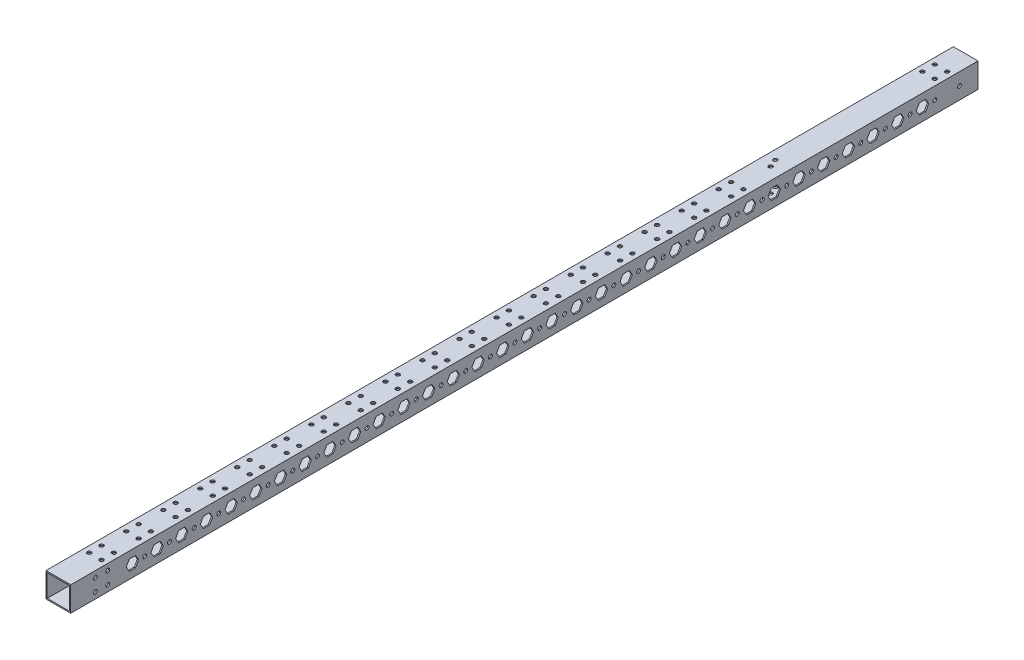
SolidWorks part; units mm, degrees
ref_plane "前视基准面" through (0, 0, 0) normal (0, 0, 1) x (1, 0, 0)
ref_plane "上视基准面" through (0, 0, 0) normal (0, 1, 0) x (1, 0, 0)
ref_plane "右视基准面" through (0, 0, 0) normal (1, 0, 0) x (0, 0, -1)
other "Configuration Table"
sketch "草图1" plane through (0, 0, 0) normal (0, 0, 1) x (1, 0, 0)
  line L1 (0, 0) -> (20, 0)
  line L2 (0, 0) -> (0, -20)
  line L3 (0, -20) -> (20, -20)
  line L4 (20, 0) -> (20, -20)
  dimension "D1" = 20
  dimension "D2" = 20
extrude "拉伸-薄壁1" add sketch "草图1" along normal blind 735 thin
sketch "草图2" plane through (20, 0, 0) normal (1, 0, 0) x (0, 0, -1)
  line L0 (-10, 0) -> (-10, -20) construction
  line L1 (0, -20) -> (0, 0) construction
  line L2 (-15, -10) -> (0, -10) construction
  line L3 (-710, 0) -> (-710, -20) construction
  line L4 (-735, 0) -> (0, 0) construction
  line L5 (-735, -20) -> (0, -20) construction
  line L6 (-735, -20) -> (-735, 0) construction
  line L7 (-710, -10) -> (-735, -10) construction
  line L8 (-20, 0) -> (-20, -20) construction
  line L9 (-35, -10) -> (-55, -10) construction
  line L10 (-47.5, -5.6699) -> (-50, -10)
  line L11 (-50, -10) -> (-47.5, -14.3301)
  line L12 (-47.5, -14.3301) -> (-42.5, -14.3301)
  line L13 (-42.5, -14.3301) -> (-40, -10)
  line L14 (-40, -10) -> (-42.5, -5.6699)
  line L15 (-42.5, -5.6699) -> (-47.5, -5.6699)
  line L16 (-62.5, -5.6699) -> (-67.5, -5.6699)
  line L17 (-60, -10) -> (-62.5, -5.6699)
  line L18 (-62.5, -14.3301) -> (-60, -10)
  line L19 (-67.5, -14.3301) -> (-62.5, -14.3301)
  line L20 (-67.5, -5.6699) -> (-70, -10)
  line L21 (-70, -10) -> (-67.5, -14.3301)
  line L22 (-82.5, -5.6699) -> (-87.5, -5.6699)
  line L23 (-80, -10) -> (-82.5, -5.6699)
  line L24 (-82.5, -14.3301) -> (-80, -10)
  line L25 (-87.5, -14.3301) -> (-82.5, -14.3301)
  line L26 (-87.5, -5.6699) -> (-90, -10)
  line L27 (-90, -10) -> (-87.5, -14.3301)
  line L28 (-102.5, -5.6699) -> (-107.5, -5.6699)
  line L29 (-100, -10) -> (-102.5, -5.6699)
  line L30 (-102.5, -14.3301) -> (-100, -10)
  line L31 (-107.5, -14.3301) -> (-102.5, -14.3301)
  line L32 (-107.5, -5.6699) -> (-110, -10)
  line L33 (-110, -10) -> (-107.5, -14.3301)
  line L34 (-122.5, -5.6699) -> (-127.5, -5.6699)
  line L35 (-120, -10) -> (-122.5, -5.6699)
  line L36 (-122.5, -14.3301) -> (-120, -10)
  line L37 (-127.5, -14.3301) -> (-122.5, -14.3301)
  line L38 (-127.5, -5.6699) -> (-130, -10)
  line L39 (-130, -10) -> (-127.5, -14.3301)
  line L40 (-142.5, -5.6699) -> (-147.5, -5.6699)
  line L41 (-140, -10) -> (-142.5, -5.6699)
  line L42 (-142.5, -14.3301) -> (-140, -10)
  line L43 (-147.5, -14.3301) -> (-142.5, -14.3301)
  line L44 (-147.5, -5.6699) -> (-150, -10)
  line L45 (-150, -10) -> (-147.5, -14.3301)
  line L46 (-162.5, -5.6699) -> (-167.5, -5.6699)
  line L47 (-160, -10) -> (-162.5, -5.6699)
  line L48 (-162.5, -14.3301) -> (-160, -10)
  line L49 (-167.5, -14.3301) -> (-162.5, -14.3301)
  line L50 (-167.5, -5.6699) -> (-170, -10)
  line L51 (-170, -10) -> (-167.5, -14.3301)
  line L52 (-182.5, -5.6699) -> (-187.5, -5.6699)
  line L53 (-180, -10) -> (-182.5, -5.6699)
  line L54 (-182.5, -14.3301) -> (-180, -10)
  line L55 (-187.5, -14.3301) -> (-182.5, -14.3301)
  line L56 (-187.5, -5.6699) -> (-190, -10)
  line L57 (-190, -10) -> (-187.5, -14.3301)
  line L58 (-202.5, -5.6699) -> (-207.5, -5.6699)
  line L59 (-200, -10) -> (-202.5, -5.6699)
  line L60 (-202.5, -14.3301) -> (-200, -10)
  line L61 (-207.5, -14.3301) -> (-202.5, -14.3301)
  line L62 (-207.5, -5.6699) -> (-210, -10)
  line L63 (-210, -10) -> (-207.5, -14.3301)
  line L64 (-222.5, -5.6699) -> (-227.5, -5.6699)
  line L65 (-220, -10) -> (-222.5, -5.6699)
  line L66 (-222.5, -14.3301) -> (-220, -10)
  line L67 (-227.5, -14.3301) -> (-222.5, -14.3301)
  line L68 (-227.5, -5.6699) -> (-230, -10)
  line L69 (-230, -10) -> (-227.5, -14.3301)
  line L70 (-242.5, -5.6699) -> (-247.5, -5.6699)
  line L71 (-240, -10) -> (-242.5, -5.6699)
  line L72 (-242.5, -14.3301) -> (-240, -10)
  line L73 (-247.5, -14.3301) -> (-242.5, -14.3301)
  line L74 (-247.5, -5.6699) -> (-250, -10)
  line L75 (-250, -10) -> (-247.5, -14.3301)
  line L76 (-262.5, -5.6699) -> (-267.5, -5.6699)
  line L77 (-260, -10) -> (-262.5, -5.6699)
  line L78 (-262.5, -14.3301) -> (-260, -10)
  line L79 (-267.5, -14.3301) -> (-262.5, -14.3301)
  line L80 (-267.5, -5.6699) -> (-270, -10)
  line L81 (-270, -10) -> (-267.5, -14.3301)
  line L82 (-282.5, -5.6699) -> (-287.5, -5.6699)
  line L83 (-280, -10) -> (-282.5, -5.6699)
  line L84 (-282.5, -14.3301) -> (-280, -10)
  line L85 (-287.5, -14.3301) -> (-282.5, -14.3301)
  line L86 (-287.5, -5.6699) -> (-290, -10)
  line L87 (-290, -10) -> (-287.5, -14.3301)
  line L88 (-302.5, -5.6699) -> (-307.5, -5.6699)
  line L89 (-300, -10) -> (-302.5, -5.6699)
  line L90 (-302.5, -14.3301) -> (-300, -10)
  line L91 (-307.5, -14.3301) -> (-302.5, -14.3301)
  line L92 (-307.5, -5.6699) -> (-310, -10)
  line L93 (-310, -10) -> (-307.5, -14.3301)
  line L94 (-322.5, -5.6699) -> (-327.5, -5.6699)
  line L95 (-320, -10) -> (-322.5, -5.6699)
  line L96 (-322.5, -14.3301) -> (-320, -10)
  line L97 (-327.5, -14.3301) -> (-322.5, -14.3301)
  line L98 (-327.5, -5.6699) -> (-330, -10)
  line L99 (-330, -10) -> (-327.5, -14.3301)
  line L100 (-342.5, -5.6699) -> (-347.5, -5.6699)
  line L101 (-340, -10) -> (-342.5, -5.6699)
  line L102 (-342.5, -14.3301) -> (-340, -10)
  line L103 (-347.5, -14.3301) -> (-342.5, -14.3301)
  line L104 (-347.5, -5.6699) -> (-350, -10)
  line L105 (-350, -10) -> (-347.5, -14.3301)
  line L106 (-362.5, -5.6699) -> (-367.5, -5.6699)
  line L107 (-360, -10) -> (-362.5, -5.6699)
  line L108 (-362.5, -14.3301) -> (-360, -10)
  line L109 (-367.5, -14.3301) -> (-362.5, -14.3301)
  line L110 (-367.5, -5.6699) -> (-370, -10)
  line L111 (-370, -10) -> (-367.5, -14.3301)
  line L112 (-382.5, -5.6699) -> (-387.5, -5.6699)
  line L113 (-380, -10) -> (-382.5, -5.6699)
  line L114 (-382.5, -14.3301) -> (-380, -10)
  line L115 (-387.5, -14.3301) -> (-382.5, -14.3301)
  line L116 (-387.5, -5.6699) -> (-390, -10)
  line L117 (-390, -10) -> (-387.5, -14.3301)
  line L118 (-402.5, -5.6699) -> (-407.5, -5.6699)
  line L119 (-400, -10) -> (-402.5, -5.6699)
  line L120 (-402.5, -14.3301) -> (-400, -10)
  line L121 (-407.5, -14.3301) -> (-402.5, -14.3301)
  line L122 (-407.5, -5.6699) -> (-410, -10)
  line L123 (-410, -10) -> (-407.5, -14.3301)
  line L124 (-422.5, -5.6699) -> (-427.5, -5.6699)
  line L125 (-420, -10) -> (-422.5, -5.6699)
  line L126 (-422.5, -14.3301) -> (-420, -10)
  line L127 (-427.5, -14.3301) -> (-422.5, -14.3301)
  line L128 (-427.5, -5.6699) -> (-430, -10)
  line L129 (-430, -10) -> (-427.5, -14.3301)
  line L130 (-442.5, -5.6699) -> (-447.5, -5.6699)
  line L131 (-440, -10) -> (-442.5, -5.6699)
  line L132 (-442.5, -14.3301) -> (-440, -10)
  line L133 (-447.5, -14.3301) -> (-442.5, -14.3301)
  line L134 (-447.5, -5.6699) -> (-450, -10)
  line L135 (-450, -10) -> (-447.5, -14.3301)
  line L136 (-462.5, -5.6699) -> (-467.5, -5.6699)
  line L137 (-460, -10) -> (-462.5, -5.6699)
  line L138 (-462.5, -14.3301) -> (-460, -10)
  line L139 (-467.5, -14.3301) -> (-462.5, -14.3301)
  line L140 (-467.5, -5.6699) -> (-470, -10)
  line L141 (-470, -10) -> (-467.5, -14.3301)
  line L142 (-482.5, -5.6699) -> (-487.5, -5.6699)
  line L143 (-480, -10) -> (-482.5, -5.6699)
  line L144 (-482.5, -14.3301) -> (-480, -10)
  line L145 (-487.5, -14.3301) -> (-482.5, -14.3301)
  line L146 (-487.5, -5.6699) -> (-490, -10)
  line L147 (-490, -10) -> (-487.5, -14.3301)
  line L148 (-502.5, -5.6699) -> (-507.5, -5.6699)
  line L149 (-500, -10) -> (-502.5, -5.6699)
  line L150 (-502.5, -14.3301) -> (-500, -10)
  line L151 (-507.5, -14.3301) -> (-502.5, -14.3301)
  line L152 (-507.5, -5.6699) -> (-510, -10)
  line L153 (-510, -10) -> (-507.5, -14.3301)
  line L154 (-522.5, -5.6699) -> (-527.5, -5.6699)
  line L155 (-520, -10) -> (-522.5, -5.6699)
  line L156 (-522.5, -14.3301) -> (-520, -10)
  line L157 (-527.5, -14.3301) -> (-522.5, -14.3301)
  line L158 (-527.5, -5.6699) -> (-530, -10)
  line L159 (-530, -10) -> (-527.5, -14.3301)
  line L160 (-542.5, -5.6699) -> (-547.5, -5.6699)
  line L161 (-540, -10) -> (-542.5, -5.6699)
  line L162 (-542.5, -14.3301) -> (-540, -10)
  line L163 (-547.5, -14.3301) -> (-542.5, -14.3301)
  line L164 (-547.5, -5.6699) -> (-550, -10)
  line L165 (-550, -10) -> (-547.5, -14.3301)
  line L166 (-562.5, -5.6699) -> (-567.5, -5.6699)
  line L167 (-560, -10) -> (-562.5, -5.6699)
  line L168 (-562.5, -14.3301) -> (-560, -10)
  line L169 (-567.5, -14.3301) -> (-562.5, -14.3301)
  line L170 (-567.5, -5.6699) -> (-570, -10)
  line L171 (-570, -10) -> (-567.5, -14.3301)
  line L172 (-582.5, -5.6699) -> (-587.5, -5.6699)
  line L173 (-580, -10) -> (-582.5, -5.6699)
  line L174 (-582.5, -14.3301) -> (-580, -10)
  line L175 (-587.5, -14.3301) -> (-582.5, -14.3301)
  line L176 (-587.5, -5.6699) -> (-590, -10)
  line L177 (-590, -10) -> (-587.5, -14.3301)
  line L178 (-602.5, -5.6699) -> (-607.5, -5.6699)
  line L179 (-600, -10) -> (-602.5, -5.6699)
  line L180 (-602.5, -14.3301) -> (-600, -10)
  line L181 (-607.5, -14.3301) -> (-602.5, -14.3301)
  line L182 (-607.5, -5.6699) -> (-610, -10)
  line L183 (-610, -10) -> (-607.5, -14.3301)
  line L184 (-622.5, -5.6699) -> (-627.5, -5.6699)
  line L185 (-620, -10) -> (-622.5, -5.6699)
  line L186 (-622.5, -14.3301) -> (-620, -10)
  line L187 (-627.5, -14.3301) -> (-622.5, -14.3301)
  line L188 (-627.5, -5.6699) -> (-630, -10)
  line L189 (-630, -10) -> (-627.5, -14.3301)
  line L190 (-642.5, -5.6699) -> (-647.5, -5.6699)
  line L191 (-640, -10) -> (-642.5, -5.6699)
  line L192 (-642.5, -14.3301) -> (-640, -10)
  line L193 (-647.5, -14.3301) -> (-642.5, -14.3301)
  line L194 (-647.5, -5.6699) -> (-650, -10)
  line L195 (-650, -10) -> (-647.5, -14.3301)
  line L196 (-662.5, -5.6699) -> (-667.5, -5.6699)
  line L197 (-660, -10) -> (-662.5, -5.6699)
  line L198 (-662.5, -14.3301) -> (-660, -10)
  line L199 (-667.5, -14.3301) -> (-662.5, -14.3301)
  line L200 (-667.5, -5.6699) -> (-670, -10)
  line L201 (-670, -10) -> (-667.5, -14.3301)
  line L202 (-682.5, -5.6699) -> (-687.5, -5.6699)
  line L203 (-680, -10) -> (-682.5, -5.6699)
  line L204 (-682.5, -14.3301) -> (-680, -10)
  line L205 (-687.5, -14.3301) -> (-682.5, -14.3301)
  line L206 (-687.5, -5.6699) -> (-690, -10)
  line L207 (-690, -10) -> (-687.5, -14.3301)
  circle A34 centre (-715, -5) radius 1.575
  circle A35 centre (-705, -5) radius 1.575
  circle A36 centre (-705, -15) radius 1.575
  circle A37 centre (-715, -15) radius 1.575
  circle A42 centre (-55, -10) radius 1.575
  circle A43 centre (-75, -10) radius 1.575
  circle A44 centre (-95, -10) radius 1.575
  circle A45 centre (-115, -10) radius 1.575
  circle A46 centre (-135, -10) radius 1.575
  circle A47 centre (-155, -10) radius 1.575
  circle A48 centre (-175, -10) radius 1.575
  circle A49 centre (-195, -10) radius 1.575
  circle A50 centre (-215, -10) radius 1.575
  circle A51 centre (-235, -10) radius 1.575
  circle A52 centre (-255, -10) radius 1.575
  circle A53 centre (-275, -10) radius 1.575
  circle A54 centre (-295, -10) radius 1.575
  circle A55 centre (-315, -10) radius 1.575
  circle A56 centre (-335, -10) radius 1.575
  circle A57 centre (-355, -10) radius 1.575
  circle A58 centre (-375, -10) radius 1.575
  circle A59 centre (-395, -10) radius 1.575
  circle A60 centre (-415, -10) radius 1.575
  circle A61 centre (-435, -10) radius 1.575
  circle A62 centre (-455, -10) radius 1.575
  circle A63 centre (-475, -10) radius 1.575
  circle A64 centre (-495, -10) radius 1.575
  circle A65 centre (-515, -10) radius 1.575
  circle A67 centre (-35, -10) radius 1.575
  circle A100 centre (-535, -10) radius 1.575
  circle A101 centre (-555, -10) radius 1.575
  circle A102 centre (-575, -10) radius 1.575
  circle A103 centre (-595, -10) radius 1.575
  circle A104 centre (-615, -10) radius 1.575
  circle A105 centre (-635, -10) radius 1.575
  circle A106 centre (-655, -10) radius 1.575
  circle A107 centre (-675, -10) radius 1.575
  circle A108 centre (-15, -10) radius 1.575
  circle A113 centre (-45, -10) radius 4.3301 construction
  circle A114 centre (-65, -10) radius 4.3301 construction
  circle A115 centre (-85, -10) radius 4.3301 construction
  circle A116 centre (-105, -10) radius 4.3301 construction
  circle A117 centre (-125, -10) radius 4.3301 construction
  circle A118 centre (-145, -10) radius 4.3301 construction
  circle A119 centre (-165, -10) radius 4.3301 construction
  circle A120 centre (-185, -10) radius 4.3301 construction
  circle A121 centre (-205, -10) radius 4.3301 construction
  circle A122 centre (-225, -10) radius 4.3301 construction
  circle A123 centre (-245, -10) radius 4.3301 construction
  circle A124 centre (-265, -10) radius 4.3301 construction
  circle A125 centre (-285, -10) radius 4.3301 construction
  circle A126 centre (-305, -10) radius 4.3301 construction
  circle A127 centre (-325, -10) radius 4.3301 construction
  circle A128 centre (-345, -10) radius 4.3301 construction
  circle A129 centre (-365, -10) radius 4.3301 construction
  circle A130 centre (-385, -10) radius 4.3301 construction
  circle A131 centre (-405, -10) radius 4.3301 construction
  circle A132 centre (-425, -10) radius 4.3301 construction
  circle A133 centre (-445, -10) radius 4.3301 construction
  circle A134 centre (-465, -10) radius 4.3301 construction
  circle A135 centre (-485, -10) radius 4.3301 construction
  circle A136 centre (-505, -10) radius 4.3301 construction
  circle A137 centre (-525, -10) radius 4.3301 construction
  circle A138 centre (-545, -10) radius 4.3301 construction
  circle A139 centre (-565, -10) radius 4.3301 construction
  circle A140 centre (-585, -10) radius 4.3301 construction
  circle A141 centre (-605, -10) radius 4.3301 construction
  circle A142 centre (-625, -10) radius 4.3301 construction
  circle A143 centre (-645, -10) radius 4.3301 construction
  circle A144 centre (-665, -10) radius 4.3301 construction
  circle A145 centre (-685, -10) radius 4.3301 construction
  dimension "D2" = 3.15
  dimension "D5" = 3.15
  dimension "D8" = 10
  dimension "D12" = 3.15
  dimension "D4" = 25
  dimension "D3" = 35
  dimension "D6" = 5
  dimension "D7" = 5
  dimension "D9" = 10
  dimension "D10" = 5
  dimension "D11" = 20
  dimension "D13" = 33
  dimension "D14" = 20
  dimension "D15" = 15
  dimension "D16" = 20
extrude "切除-拉伸1" cut sketch "草图2" against normal through all
sketch "草图3" plane through (0, 0, 0) normal (0, 1, 0) x (1, 0, 0)
  line L0 (0, -400) -> (20, -400) construction
  line L1 (0, -735) -> (0, 0) construction
  line L2 (20, -735) -> (20, 0) construction
  line L3 (20, -735) -> (0, -735) construction
  line L4 (10, -400) -> (10, -735) construction
  line L5 (20, 0) -> (0, 0) construction
  line L6 (0, -25) -> (20, -25) construction
  line L7 (0, -158) -> (20, -158) construction
  line L8 (10, -158) -> (10, -146) construction
  line L9 (10, -146) -> (5, -146) construction
  line L10 (5, -146) -> (10, -158) construction
  circle A0 centre (5, -405) radius 1.6
  circle A1 centre (15, -405) radius 1.6
  circle A2 centre (15, -395) radius 1.6
  circle A3 centre (5, -395) radius 1.6
  circle A4 centre (5, -30) radius 1.6
  circle A5 centre (15, -30) radius 1.6
  circle A6 centre (15, -20) radius 1.6
  circle A7 centre (5, -20) radius 1.6
  circle A8 centre (10, -158) radius 1.6
  circle A9 centre (7.3077, -151.5385) radius 1.575
  circle A10 centre (5, -425) radius 1.6
  circle A11 centre (15, -425) radius 1.6
  circle A12 centre (15, -435) radius 1.6
  circle A13 centre (5, -435) radius 1.6
  circle A14 centre (5, -455) radius 1.6
  circle A15 centre (15, -455) radius 1.6
  circle A16 centre (15, -465) radius 1.6
  circle A17 centre (5, -465) radius 1.6
  circle A18 centre (5, -485) radius 1.6
  circle A19 centre (15, -485) radius 1.6
  circle A20 centre (15, -495) radius 1.6
  circle A21 centre (5, -495) radius 1.6
  circle A22 centre (5, -515) radius 1.6
  circle A23 centre (15, -515) radius 1.6
  circle A24 centre (15, -525) radius 1.6
  circle A25 centre (5, -525) radius 1.6
  circle A26 centre (5, -545) radius 1.6
  circle A27 centre (15, -545) radius 1.6
  circle A28 centre (15, -555) radius 1.6
  circle A29 centre (5, -555) radius 1.6
  circle A30 centre (5, -575) radius 1.6
  circle A31 centre (15, -575) radius 1.6
  circle A32 centre (15, -585) radius 1.6
  circle A33 centre (5, -585) radius 1.6
  circle A34 centre (5, -605) radius 1.6
  circle A35 centre (15, -605) radius 1.6
  circle A36 centre (15, -615) radius 1.6
  circle A37 centre (5, -615) radius 1.6
  circle A38 centre (5, -635) radius 1.6
  circle A39 centre (15, -635) radius 1.6
  circle A40 centre (15, -645) radius 1.6
  circle A41 centre (5, -645) radius 1.6
  circle A42 centre (5, -665) radius 1.6
  circle A43 centre (15, -665) radius 1.6
  circle A44 centre (15, -675) radius 1.6
  circle A45 centre (5, -675) radius 1.6
  circle A46 centre (5, -695) radius 1.6
  circle A47 centre (15, -695) radius 1.6
  circle A48 centre (15, -705) radius 1.6
  circle A49 centre (5, -705) radius 1.6
  circle A50 centre (5, -185) radius 1.6
  circle A51 centre (15, -185) radius 1.6
  circle A52 centre (15, -195) radius 1.6
  circle A53 centre (5, -195) radius 1.6
  circle A54 centre (5, -215) radius 1.6
  circle A55 centre (15, -215) radius 1.6
  circle A56 centre (15, -225) radius 1.6
  circle A57 centre (5, -225) radius 1.6
  circle A58 centre (5, -245) radius 1.6
  circle A59 centre (15, -245) radius 1.6
  circle A60 centre (15, -255) radius 1.6
  circle A61 centre (5, -255) radius 1.6
  circle A62 centre (5, -275) radius 1.6
  circle A63 centre (15, -275) radius 1.6
  circle A64 centre (15, -285) radius 1.6
  circle A65 centre (5, -285) radius 1.6
  circle A66 centre (5, -305) radius 1.6
  circle A67 centre (15, -305) radius 1.6
  circle A68 centre (15, -315) radius 1.6
  circle A69 centre (5, -315) radius 1.6
  circle A70 centre (5, -335) radius 1.6
  circle A71 centre (15, -335) radius 1.6
  circle A72 centre (15, -345) radius 1.6
  circle A73 centre (5, -345) radius 1.6
  circle A74 centre (5, -365) radius 1.6
  circle A75 centre (15, -365) radius 1.6
  circle A76 centre (15, -375) radius 1.6
  circle A77 centre (5, -375) radius 1.6
  dimension "D2" = 3.2
  dimension "D5" = 3.2
  dimension "D10" = 3.2
  dimension "D13" = 3.15
  dimension "D1" = 400
  dimension "D3" = 5
  dimension "D4" = 5
  dimension "D6" = 25
  dimension "D7" = 5
  dimension "D8" = 5
  dimension "D9" = 158
  dimension "D11" = 5
  dimension "D12" = 12
  dimension "D14" = 7
  dimension "D15" = 30
extrude "切除-拉伸2" cut sketch "草图3" against normal through all
